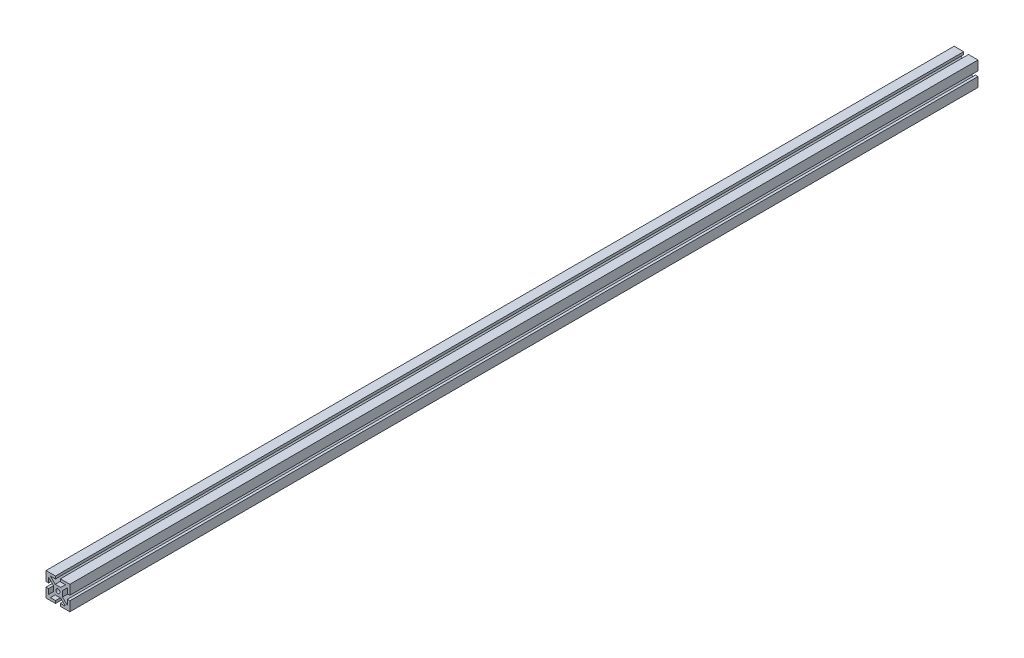
SolidWorks part; units mm, degrees
material "6061-T6 (SS)"
ref_plane "Front Plane" through (0, 0, 0) normal (0, 0, 1) x (1, 0, 0)
ref_plane "Top Plane" through (0, 0, 0) normal (0, 1, 0) x (1, 0, 0)
ref_plane "Right Plane" through (0, 0, 0) normal (1, 0, 0) x (0, 0, -1)
sketch "Sketch1" plane through (0, 0, 0) normal (0, 0, 1) x (1, 0, 0)
  line L0 (0, 0) -> (15.94, 0)
  line L1 (15.94, 0) -> (15.94, 4.32)
  line L2 (15.94, 4.32) -> (7.3747, 4.32)
  line L3 (7.3747, 4.32) -> (15.3697, 12.315)
  line L4 (15.3697, 12.315) -> (12.315, 12.315) construction
  line L5 (12.315, 12.315) -> (12.315, 15.3697) construction
  line L6 (12.315, 15.3697) -> (4.32, 7.3747)
  line L7 (4.32, 7.3747) -> (4.32, 15.94)
  line L8 (4.32, 15.94) -> (0, 15.94)
  line L9 (0, 15.94) -> (0, 0)
  line L10 (0, 0) -> (12.315, 12.315) construction
  line L11 (20, 0) -> (20, 4.32) construction
  line L12 (15.94, 0) -> (20, 0) construction
  line L13 (15.94, 4.32) -> (20, 4.32) construction
  line L14 (40, 0) -> (27.685, 12.315) construction
  line L15 (40, 15.94) -> (40, 0)
  line L16 (35.68, 15.94) -> (40, 15.94)
  line L17 (35.68, 7.3747) -> (35.68, 15.94)
  line L18 (27.685, 15.3697) -> (35.68, 7.3747)
  line L19 (27.685, 12.315) -> (27.685, 15.3697) construction
  line L20 (24.6303, 12.315) -> (27.685, 12.315) construction
  line L21 (32.6253, 4.32) -> (24.6303, 12.315)
  line L22 (24.06, 4.32) -> (32.6253, 4.32)
  line L23 (24.06, 0) -> (24.06, 4.32)
  line L24 (40, 0) -> (24.06, 0)
  line L25 (4.32, 15.94) -> (4.32, 20) construction
  line L26 (4.32, 20) -> (0, 20) construction
  line L27 (0, 20) -> (0, 15.94) construction
  line L28 (40, 40) -> (27.685, 27.685) construction
  line L29 (15.94, 35.68) -> (20, 35.68) construction
  line L30 (15.94, 40) -> (20, 40) construction
  line L31 (20, 40) -> (20, 35.68) construction
  line L32 (0, 40) -> (12.315, 27.685) construction
  line L33 (40, 40) -> (24.06, 40)
  line L34 (24.06, 40) -> (24.06, 35.68)
  line L35 (24.06, 35.68) -> (32.6253, 35.68)
  line L36 (32.6253, 35.68) -> (24.6303, 27.685)
  line L37 (24.6303, 27.685) -> (27.685, 27.685) construction
  line L38 (27.685, 27.685) -> (27.685, 24.6303) construction
  line L39 (27.685, 24.6303) -> (35.68, 32.6253)
  line L40 (35.68, 32.6253) -> (35.68, 24.06)
  line L41 (35.68, 24.06) -> (40, 24.06)
  line L42 (40, 24.06) -> (40, 40)
  line L43 (0, 24.06) -> (0, 40)
  line L44 (4.32, 24.06) -> (0, 24.06)
  line L45 (4.32, 32.6253) -> (4.32, 24.06)
  line L46 (12.315, 24.6303) -> (4.32, 32.6253)
  line L47 (12.315, 27.685) -> (12.315, 24.6303) construction
  line L48 (15.3697, 27.685) -> (12.315, 27.685) construction
  line L49 (7.3747, 35.68) -> (15.3697, 27.685)
  line L50 (15.94, 35.68) -> (7.3747, 35.68)
  line L51 (15.94, 40) -> (15.94, 35.68)
  line L52 (0, 40) -> (15.94, 40)
  line L53 (12.315, 24.6303) -> (12.315, 15.3697)
  line L54 (15.3697, 12.315) -> (24.6303, 12.315)
  line L55 (12.315, 20) -> (27.685, 20) construction
  line L56 (27.685, 15.3697) -> (27.685, 24.6303)
  line L57 (15.3697, 27.685) -> (24.6303, 27.685)
  circle A0 centre (20, 20) radius 3.4
  dimension "D7" = 6.8
  dimension "D1" = 4.32
  dimension "D2" = 4.32
  dimension "D3" = 45
  dimension "D4" = 8.12
  dimension "D5" = 40
  dimension "D6" = 15.37
extrude "Boss-Extrude1" add sketch "Sketch1" along normal blind 1524
